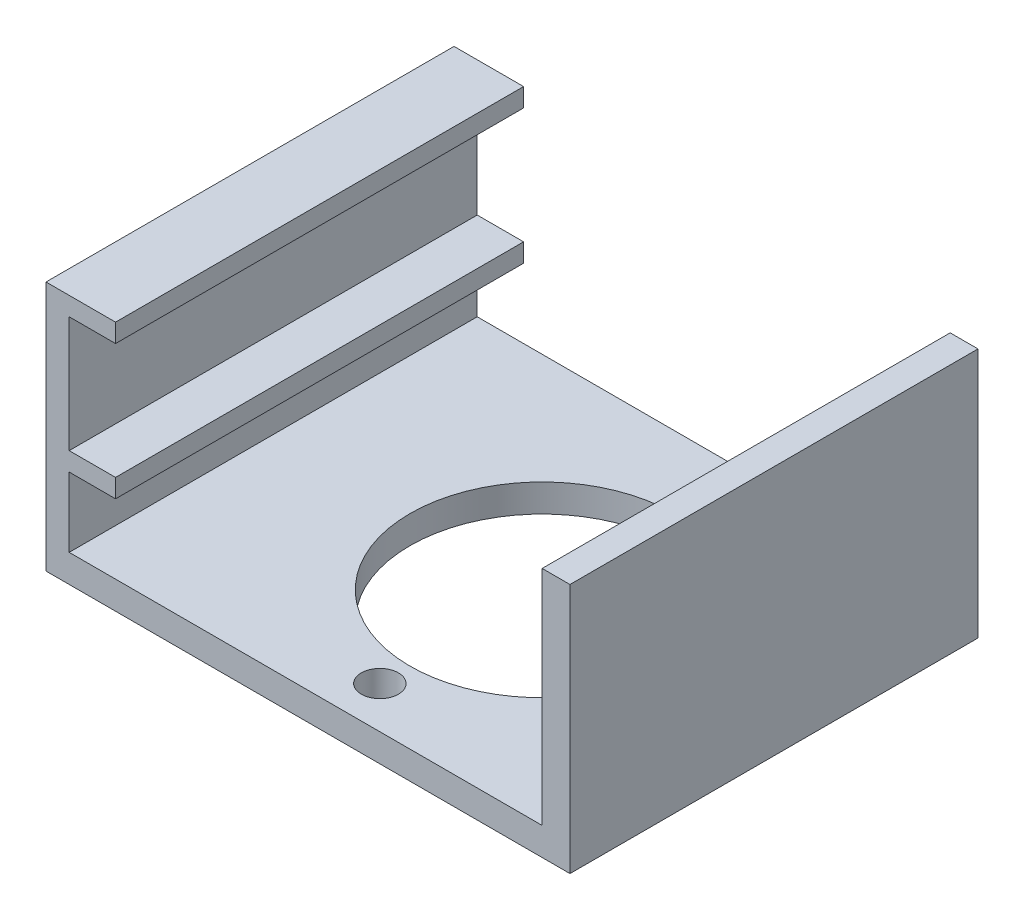
SolidWorks part; units mm, degrees
ref_plane "Front Plane" through (0, 0, 0) normal (0, 0, 1) x (1, 0, 0)
ref_plane "Top Plane" through (0, 0, 0) normal (0, 1, 0) x (1, 0, 0)
ref_plane "Right Plane" through (0, 0, 0) normal (1, 0, 0) x (0, 0, -1)
sketch "Sketch1" plane through (0, 0, 0) normal (0, 1, 0) x (1, 0, 0)
  line L1 (-23.0791, 14.3848) -> (26.9209, 14.3848)
  line L2 (-23.0791, 14.3848) -> (-23.0791, -25.6152)
  line L3 (-23.0791, -25.6152) -> (26.9209, -25.6152)
  line L4 (26.9209, 14.3848) -> (26.9209, -25.6152)
  dimension "D1" = 50
  dimension "D2" = 40
extrude "Boss-Extrude1" add sketch "Sketch1" along normal blind 3
sketch "Sketch2" plane through (0, 3, 0) normal (0, 1, 0) x (1, 0, 0)
  line L0 (-19.0791, 14.3848) -> (-19.0791, -25.6152)
  line L1 (26.9209, 14.3848) -> (-23.0791, 14.3848) construction
  line L2 (-23.0791, -25.6152) -> (26.9209, -25.6152) construction
  line L7 (-23.0791, 14.3848) -> (-23.0791, -25.6152)
  line L8 (-23.0791, -25.6152) -> (26.9209, -25.6152)
  line L9 (26.9209, -25.6152) -> (26.9209, 14.3848)
  line L10 (26.9209, 14.3848) -> (-23.0791, 14.3848)
  line L11 (-23.0791, 14.3848) -> (-23.0791, -25.6152)
  line L12 (-23.0791, -25.6152) -> (-19.0791, -25.6152)
  line L14 (-19.0791, 14.3848) -> (-23.0791, 14.3848)
  dimension "D1" = 0
  dimension "D2" = 4
extrude "Boss-Extrude2" add sketch "Sketch2" along normal blind 24
sketch "Sketch3" plane through (-19.0791, 0, 0) normal (1, 0, 0) x (0, 0, -1)
  line L0 (-25.6152, 27) -> (-25.6152, 3) construction
  line L1 (-25.6152, 25) -> (14.3848, 25)
  line L2 (-25.6152, 25) -> (-25.6152, 12)
  line L3 (-25.6152, 12) -> (14.3848, 12)
  line L4 (14.3848, 25) -> (14.3848, 12)
  line L5 (14.3848, 27) -> (14.3848, 3) construction
  line L6 (-25.6152, 27) -> (14.3848, 27) construction
  dimension "D1" = 2
  dimension "D2" = 13
extrude "Cut-Extrude1" cut sketch "Sketch3" against normal blind 2
sketch "Sketch5" plane through (0, 3, 0) normal (0, 1, 0) x (1, 0, 0)
  line L0 (24.9209, 14.3848) -> (24.9209, -25.6152)
  line L1 (26.9209, 14.3848) -> (-19.0791, 14.3848) construction
  line L2 (-19.0791, -25.6152) -> (26.9209, -25.6152) construction
  line L7 (-19.0791, 14.3848) -> (-19.0791, -25.6152)
  line L8 (-19.0791, -25.6152) -> (26.9209, -25.6152)
  line L9 (26.9209, -25.6152) -> (26.9209, 14.3848)
  line L10 (26.9209, 14.3848) -> (-19.0791, 14.3848)
  line L12 (24.9209, -25.6152) -> (26.9209, -25.6152)
  line L13 (26.9209, -25.6152) -> (26.9209, 14.3848)
  line L14 (26.9209, 14.3848) -> (24.9209, 14.3848)
  dimension "D1" = 0
  dimension "D2" = 2
extrude "Boss-Extrude3" add sketch "Sketch5" along normal blind 24
sketch "Sketch6" plane through (0, 0, 0) normal (0, -1, 0) x (1, 0, 0)
  line L0 (-23.0791, 5.6152) -> (-1.0791, 5.6152)
  line L1 (-23.0791, -14.3848) -> (-23.0791, 25.6152) construction
  line L2 (6.9209, 5.6152) -> (6.9209, -11.8848)
  line L3 (-1.0791, 5.6152) -> (6.9209, 5.6152)
  line L4 (6.9209, 5.6152) -> (6.9209, 23.1152)
  line L5 (24.4209, 13.0152) -> (18.923, 13.0152)
  line L6 (6.9209, 5.6152) -> (24.4209, 5.6152)
  line L7 (24.4209, 5.6152) -> (24.4209, 13.0152)
  line L8 (24.4209, 5.6152) -> (24.4209, -1.7848)
  line L9 (24.4209, -1.7848) -> (18.923, -1.7848)
  arc A1 (18.923, 13.0152) -> (18.923, -1.7848) centre (6.9209, 5.6152) ccw
  circle A2 centre (6.9209, 23.1152) radius 2
  circle A3 centre (6.9209, -11.8848) radius 2
  dimension "D2" = 8
  dimension "D3" = 17.5
  dimension "D5" = 17.5
  dimension "D1" = 22
  dimension "D4" = 17.5
extrude "Cut-Extrude9" cut sketch "Sketch6" against normal blind 5
sketch "Sketch9" plane through (0, 0, 25.6152) normal (0, 0, 1) x (1, 0, 0)
sketch "Sketch10" plane through (0, 0, 25.6152) normal (0, 0, 1) x (1, 0, 0)
  line L0 (-19.0791, 27) -> (-19.0791, 25)
  line L1 (-19.0791, 25) -> (-21.0791, 25)
  line L2 (-21.0791, 25) -> (-21.0791, 12)
  line L3 (-21.0791, 12) -> (-19.0791, 12)
  line L4 (-19.0791, 12) -> (-19.0791, 3)
  line L5 (-19.0791, 3) -> (24.9209, 3)
  line L6 (24.9209, 3) -> (24.9209, 27)
  line L7 (24.9209, 27) -> (26.9209, 27)
  line L8 (26.9209, 27) -> (26.9209, 0)
  line L9 (26.9209, 0) -> (-23.0791, 0)
  line L10 (-23.0791, 0) -> (-23.0791, 27)
  line L11 (-23.0791, 27) -> (-19.0791, 27)
extrude "Boss-Extrude5" add sketch "Sketch10" along normal blind 2
sketch "Sketch11" plane through (0, 0, -14.3848) normal (0, 0, -1) x (-1, 0, 0)
  line L0 (-26.9209, 27) -> (-24.9209, 27)
  line L1 (-24.9209, 27) -> (-24.9209, 3)
  line L2 (-24.9209, 3) -> (19.0791, 3)
  line L3 (19.0791, 3) -> (19.0791, 12)
  line L4 (19.0791, 12) -> (21.0791, 12)
  line L5 (21.0791, 12) -> (21.0791, 25)
  line L6 (21.0791, 25) -> (19.0791, 25)
  line L7 (19.0791, 25) -> (19.0791, 27)
  line L8 (19.0791, 27) -> (23.0791, 27)
  line L9 (23.0791, 27) -> (23.0791, 0)
  line L10 (55, 0) -> (-55, 0) construction
  line L11 (23.0791, 27) -> (23.0791, 0) construction
  line L12 (23.0791, 0) -> (-26.9209, 0)
  line L13 (-26.9209, 0) -> (-26.9209, 27)
extrude "Boss-Extrude6" add sketch "Sketch11" along normal blind 2
sketch "Sketch12" plane through (26.9209, 0, 0) normal (1, 0, 0) x (0, 0, -1)
  line L0 (55, 0) -> (-55, 0) construction
  line L1 (-27.6152, 27) -> (16.3848, 27)
  line L2 (-27.6152, 27) -> (-27.6152, 0)
  line L3 (-27.6152, 0) -> (16.3848, 0)
  line L4 (16.3848, 27) -> (16.3848, 0)
  line L5 (16.3848, 27) -> (16.3848, 0) construction
extrude "Boss-Extrude7" add sketch "Sketch12" along normal blind 1
sketch "Sketch14" plane through (-19.0791, 0, 0) normal (1, 0, 0) x (0, 0, -1)
  line L1 (-27.6152, 25) -> (16.3848, 25)
  line L2 (-27.6152, 25) -> (-27.6152, 27)
  line L3 (-27.6152, 27) -> (16.3848, 27)
  line L4 (16.3848, 25) -> (16.3848, 27)
extrude "Boss-Extrude8" add sketch "Sketch14" along normal blind 3
sketch3d "3DSketch1"
  line L1 (-21.0791, 12, 27.6152) -> (-19.0791, 12, 27.6152)
  line L2 (-21.0791, 12, 27.6152) -> (-21.0791, 12, -16.3848)
  line L3 (-21.0791, 12, -16.3848) -> (-19.0791, 12, -16.3848)
  line L4 (-19.0791, 12, 27.6152) -> (-19.0791, 12, -16.3848)
extrude "Boss-Extrude9" add sketch "3DSketch1" along direction (0, -1, 0) on the side against the normal blind 0.5
sketch "Sketch15" plane through (-19.0791, 0, 0) normal (1, 0, 0) x (0, 0, -1)
  line L0 (16.3848, 12.5) -> (16.3848, 3) construction
  line L1 (-27.6152, 12.5) -> (16.3848, 12.5)
  line L2 (-27.6152, 12.5) -> (-27.6152, 10.5)
  line L3 (-27.6152, 10.5) -> (16.3848, 10.5)
  line L4 (16.3848, 12.5) -> (16.3848, 10.5)
  dimension "D1" = 2
extrude "Boss-Extrude10" add sketch "Sketch15" along normal blind 3 contours L2 L1 L4 L3
sketch "Sketch16" plane through (24.4209, 0, 0) normal (-1, 0, 0) x (0, 0, 1)
  line L1 (13.0152, 0) -> (-1.7848, 0)
  line L2 (13.0152, 0) -> (13.0152, 3)
  line L3 (13.0152, 3) -> (-1.7848, 3)
  line L4 (-1.7848, 0) -> (-1.7848, 3)
extrude "Cut-Extrude10" cut sketch "Sketch16" against normal blind 0.5
sketch "Sketch17" plane through (27.9209, 0, 0) normal (1, 0, 0) x (0, 0, -1)
  line L0 (55, 0) -> (-55, 0) construction
  line L1 (-27.6152, 27) -> (16.3848, 27)
  line L2 (-27.6152, 27) -> (-27.6152, 0)
  line L3 (-27.6152, 0) -> (16.3848, 0)
  line L4 (16.3848, 27) -> (16.3848, 0)
  line L5 (16.3848, 0) -> (16.3848, 27) construction
extrude "Boss-Extrude11" add sketch "Sketch17" along normal blind 4
sketch "Sketch18" plane through (24.9209, 0, 0) normal (-1, 0, 0) x (0, 0, 1)
  line L1 (-16.3848, 3) -> (27.6152, 3)
  line L2 (-16.3848, 3) -> (-16.3848, 27)
  line L3 (-16.3848, 27) -> (27.6152, 27)
  line L4 (27.6152, 3) -> (27.6152, 27)
extrude "Cut-Extrude11" cut sketch "Sketch18" against normal blind 4
sketch "Sketch21" plane through (0, 0, 0) normal (0, -1, 0) x (-1, 0, 0)
  circle A0 centre (-6.9209, -5.6152) radius 14.25
extrude "Cut-Extrude15" cut sketch "Sketch21" against normal blind 4
sketch "Sketch22" plane through (0, 3, 0) normal (0, 1, 0) x (1, 0, 0)
  line L0 (24.9209, 4.1848) -> (17.2661, 4.1848)
  line L1 (24.9209, -15.4152) -> (17.2661, -15.4152)
  line L2 (19.0989, 1.7848) -> (24.9209, 1.7848) construction
  line L3 (19.0989, -13.0152) -> (24.9209, -13.0152) construction
  circle A0 centre (6.9209, -5.6152) radius 15.9999
  arc A1 (19.0989, 1.7848) -> (19.0989, -13.0152) centre (6.9209, -5.6152) ccw construction
  arc M4 (19.0989, -13.0152) -> (19.0989, 1.7848) centre (6.9209, -5.6152) cw
  line M5 (19.0989, 1.7848) -> (24.9209, 1.7848)
  line M7 (24.9209, -13.0152) -> (19.0989, -13.0152)
  dimension "D1" = 2.4
  dimension "D2" = 2.4
extrude "Cut-Extrude16" cut sketch "Sketch22" against normal blind 4 contours A0 L0 M5 M4 | L1 A0 M7 M4
sketch "Sketch24" plane through (-23.0791, 0, 0) normal (-1, 0, 0) x (0, 0, 1)
  line L0 (55, 0) -> (-55, 0) construction
  line L1 (-16.3848, 27) -> (27.6152, 27)
  line L2 (-16.3848, 27) -> (-16.3848, 0)
  line L3 (-16.3848, 0) -> (27.6152, 0)
  line L4 (27.6152, 27) -> (27.6152, 0)
extrude "Boss-Extrude13" add sketch "Sketch24" along normal blind 1
sketch "Sketch25" plane through (-21.0791, 0, 0) normal (1, 0, 0) x (0, 0, -1)
  line L1 (16.3848, 12.5) -> (-27.6152, 12.5)
  line L2 (16.3848, 12.5) -> (16.3848, 25)
  line L3 (16.3848, 25) -> (-27.6152, 25)
  line L4 (-27.6152, 12.5) -> (-27.6152, 25)
extrude "Cut-Extrude17" cut sketch "Sketch25" against normal blind 1
sketch "Sketch26" plane through (-16.0791, 0, 0) normal (1, 0, 0) x (0, 0, -1)
  line L0 (-27.6152, 27) -> (-27.6152, 25) construction
  line L1 (16.3848, 27) -> (-27.6152, 27)
  line L2 (16.3848, 27) -> (16.3848, 25)
  line L3 (16.3848, 25) -> (-27.6152, 25)
  line L4 (-27.6152, 27) -> (-27.6152, 25)
  line L5 (-27.6152, 25) -> (16.3848, 25) construction
extrude "Cut-Extrude18" cut sketch "Sketch26" against normal blind 1
sketch "Sketch27" plane through (-16.0791, 0, 0) normal (1, 0, 0) x (0, 0, -1)
  line L1 (-27.6152, 10.5) -> (16.3848, 10.5)
  line L2 (-27.6152, 10.5) -> (-27.6152, 12.5)
  line L3 (-27.6152, 12.5) -> (16.3848, 12.5)
  line L4 (16.3848, 10.5) -> (16.3848, 12.5)
extrude "Cut-Extrude19" cut sketch "Sketch27" against normal blind 1
sketch "Sketch28" plane through (-19.0791, 0, 0) normal (1, 0, 0) x (0, 0, -1)
  line L1 (16.3848, 3) -> (-27.6152, 3)
  line L2 (16.3848, 3) -> (16.3848, 10.5)
  line L3 (16.3848, 10.5) -> (-27.6152, 10.5)
  line L4 (-27.6152, 3) -> (-27.6152, 10.5)
extrude "Cut-Extrude20" cut sketch "Sketch28" against normal blind 3
sketch "Sketch29" plane through (-24.0791, 0, 0) normal (-1, 0, 0) x (0, 0, 1)
  line L0 (55, 0) -> (-55, 0) construction
  line L1 (-16.3848, 27) -> (27.6152, 27)
  line L2 (-16.3848, 27) -> (-16.3848, 0)
  line L3 (-16.3848, 0) -> (27.6152, 0)
  line L4 (27.6152, 27) -> (27.6152, 0)
  line L5 (27.6152, 0) -> (27.6152, 27) construction
extrude "Boss-Extrude14" add sketch "Sketch29" along normal blind 0.5
